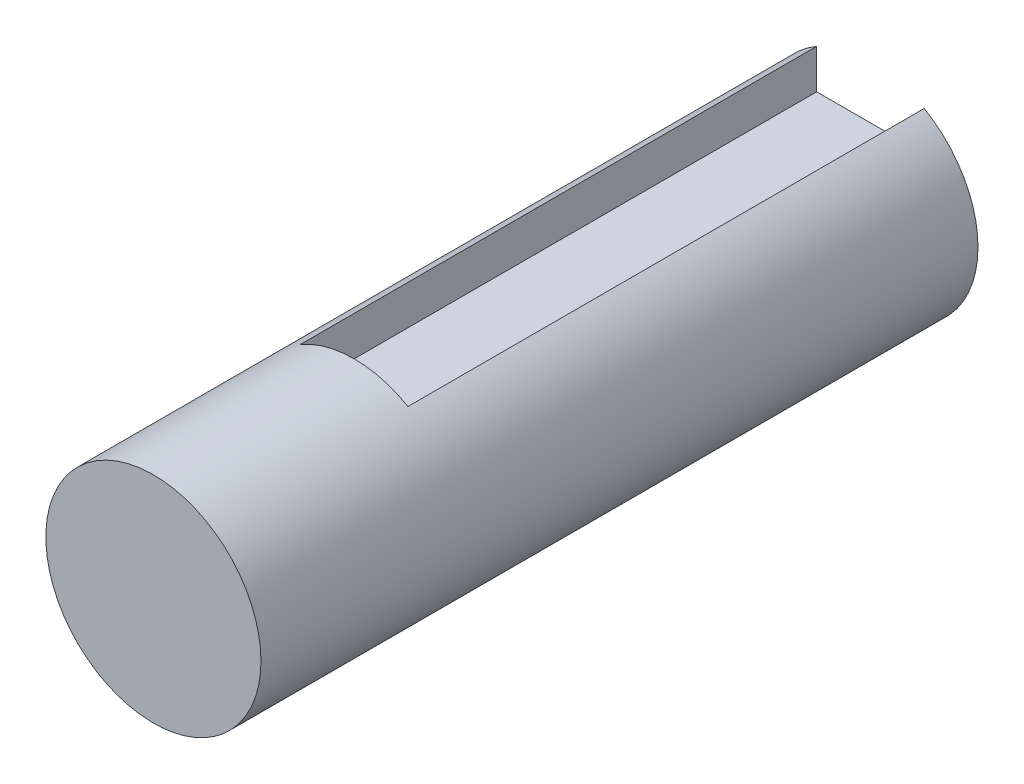
SolidWorks part; units mm, degrees
ref_plane "Front Plane" through (0, 0, 0) normal (0, 0, 1) x (1, 0, 0)
ref_plane "Top Plane" through (0, 0, 0) normal (0, 1, 0) x (1, 0, 0)
ref_plane "Right Plane" through (0, 0, 0) normal (1, 0, 0) x (0, 0, -1)
sketch "Sketch1" plane through (0, 0, 0) normal (0, 1, 0) x (1, 0, 0)
  line L0 (15, 72) -> (0, 72)
  line L1 (0, 72) -> (0, -28)
  line L2 (0, -28) -> (15, -28)
  line L3 (15, -28) -> (15, 72)
  line L4 (0, 72) -> (0, -28) construction
revolve "Revolve1" add sketch "Sketch1" angle 360 about L4
sketch "Sketch2" plane through (0, 0, -72) normal (0, 0, -1) x (-1, 0, 0)
  line L0 (-7.5, 12.9904) -> (-7.5, 7.5)
  line L1 (-7.5, 7.5) -> (7.5, 7.5)
  line L2 (7.5, 7.5) -> (7.5, 12.9904)
  arc A0 (7.5, 12.9904) -> (-7.5, 12.9904) centre (0, 0) ccw
extrude "Cut-Extrude1" cut sketch "Sketch2" against normal blind 72
